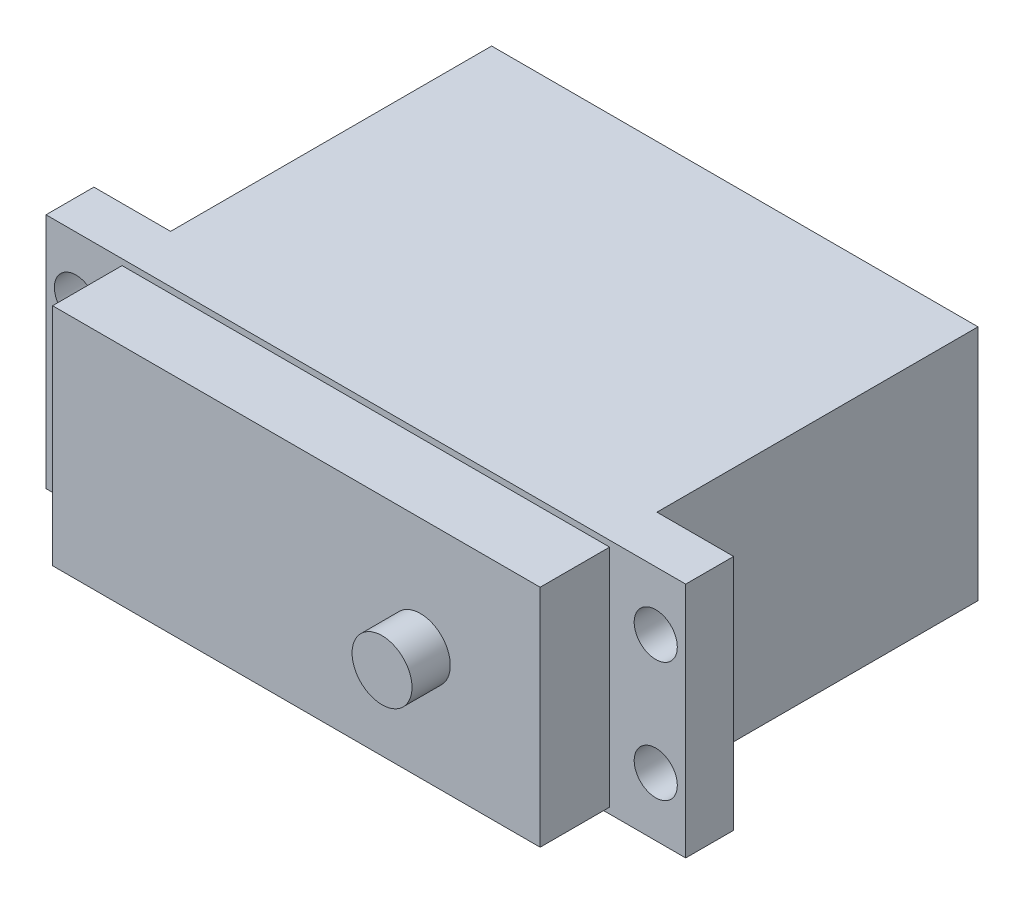
SolidWorks part; units mm, degrees
ref_plane "Front Plane" through (0, 0, 0) normal (0, 0, 1) x (1, 0, 0)
ref_plane "Top Plane" through (0, 0, 0) normal (0, 1, 0) x (1, 0, 0)
ref_plane "Right Plane" through (0, 0, 0) normal (1, 0, 0) x (0, 0, -1)
sketch "Sketch1" plane through (0, 0, 0) normal (0, 0, 1) x (1, 0, 0)
  line L1 (0, 0) -> (40.6, 0)
  line L2 (0, 0) -> (0, 19.8)
  line L3 (0, 19.8) -> (40.6, 19.8)
  line L4 (40.6, 0) -> (40.6, 19.8)
  line L5 (0, 0) -> (40.6, 19.8) construction
  line L6 (0, 19.8) -> (40.6, 0) construction
  point P4 (20.3, 9.9)
  dimension "D1" = 19.8
  dimension "D2" = 40.6
extrude "Boss-Extrude1" add sketch "Sketch1" along normal blind 26.8
sketch "Sketch2" plane through (0, 0, 26.8) normal (0, 0, 1) x (1, 0, 0)
  line L0 (0, 19.8) -> (0, 0) construction
  line L1 (47, 0) -> (-6.4, 0)
  line L2 (47, 0) -> (47, 19.8)
  line L3 (47, 19.8) -> (-6.4, 19.8)
  line L4 (-6.4, 0) -> (-6.4, 19.8)
  line L5 (47, 0) -> (-6.4, 19.8) construction
  line L6 (47, 19.8) -> (-6.4, 0) construction
  line L7 (0, 0) -> (40.6, 0) construction
  line L8 (40.6, 19.8) -> (0, 19.8) construction
  point P0 (20.3, 9.9)
  point P8 (0, 9.9)
  point P9 (20.3, 0)
  point P17 (20.3, 19.8)
  dimension "D1" = 53.4
extrude "Boss-Extrude2" add sketch "Sketch2" along normal blind 4
hole_wizard "M3 Clearance Hole1" positions "Sketch4" profile "Sketch5" hole size "M3" standard "ANSI Metric" end condition through all
sketch "Sketch4" plane through (0, 0, 30.8) normal (0, 0, 1) x (1, 0, 0)
  line L0 (20.3, 0) -> (20.3, 19.8) construction
  line L1 (-6.4, 0) -> (47, 0) construction
  line L2 (47, 19.8) -> (-6.4, 19.8) construction
  line L4 (47, 0) -> (47, 19.8) construction
  point P0 (-3.9, 14.9)
  point P2 (-3.9, 4.9)
  point P4 (44.5, 4.9)
  point P6 (44.5, 14.9)
  point P23 (47, 9.9)
  dimension "D1" = 48.4
  dimension "D2" = 24.2
  dimension "D3" = 10
  dimension "D4" = 5
sketch "Sketch5" plane through (-3.9, 14.9, 30.8) normal (1, 0, 0) x (0, -1, 0)
  line L0 (0, 0) -> (0, 30.8)
  line L1 (0, 30.8) -> (1.8, 30.8)
  line L2 (1.8, 30.8) -> (1.8, 0)
  line L5 (1.8, 0) -> (0, 0)
  line L11 (0, -6.35) -> (0, 107.95) construction
  dimension "Thru Hole Dia." = 3.6
  dimension "Thru Hole Depth" = 30.8
sketch "Sketch6" plane through (0, 0, 30.8) normal (0, 0, 1) x (1, 0, 0)
  line L0 (-6.4, 19.8) -> (-6.4, 0) construction
  line L1 (-0.05, 0.5) -> (40.65, 0.5)
  line L2 (-0.05, 0.5) -> (-0.05, 19.3)
  line L3 (-0.05, 19.3) -> (40.65, 19.3)
  line L4 (40.65, 0.5) -> (40.65, 19.3)
  line L5 (-0.05, 0.5) -> (40.65, 19.3) construction
  line L6 (-0.05, 19.3) -> (40.65, 0.5) construction
  line L7 (47, 0) -> (47, 19.8) construction
  line L8 (-6.4, 0) -> (47, 0) construction
  line L9 (47, 19.8) -> (-6.4, 19.8) construction
  point P0 (20.3, 9.9)
  dimension "D1" = 6.35
  dimension "D2" = 6.35
  dimension "D3" = 0.5
  dimension "D4" = 0.5
extrude "Boss-Extrude3" add sketch "Sketch6" along normal offset from surface (5.8 mm away) 36.6 up to face at (20.3, 9.9, 0)
sketch "Sketch7" plane through (0, 0, 36.6) normal (0, 0, 1) x (1, 0, 0)
  line L0 (40.65, 0.5) -> (40.65, 19.3) construction
  line L1 (-0.05, 0.5) -> (40.65, 0.5) construction
  circle A0 centre (30.65, 9.9) radius 2.5
  point P5 (40.65, 9.9)
  point P7 (20.3, 0.5)
  dimension "D1" = 10
  dimension "D2" = 5
  dimension "D3" = 10.35
extrude "Boss-Extrude4" add sketch "Sketch7" along normal offset from surface (3.2 mm away) 13 up to face at (-2.1, 14.9, 26.8)
